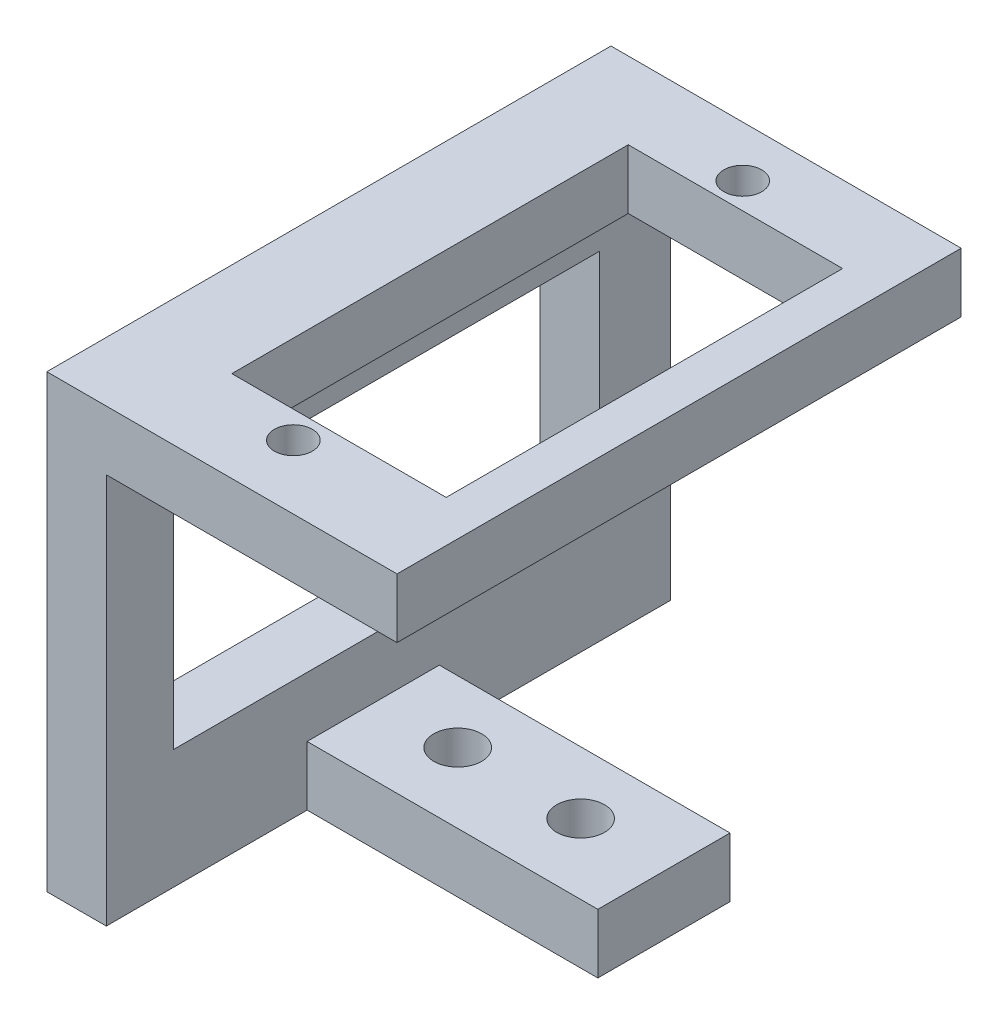
SolidWorks part; units mm, degrees
ref_plane "Front Plane" through (0, 0, 0) normal (0, 0, 1) x (1, 0, 0)
ref_plane "Top Plane" through (0, 0, 0) normal (0, 1, 0) x (1, 0, 0)
ref_plane "Right Plane" through (0, 0, 0) normal (1, 0, 0) x (0, 0, -1)
sketch "Sketch1" plane through (0, 0, 0) normal (0, 0, 1) x (1, 0, 0)
  line L0 (0, 0) -> (0, -20.0603)
  line L1 (0, -20.0603) -> (17.6, -20.0603)
  line L2 (0, 0) -> (17.6, 0)
  dimension "D1" = 20.0603
  dimension "D2" = 17.6
  dimension "D3" = 17.6
extrude "Extrude-Thin1" add sketch "Sketch1" against normal blind 34.1541 thin
sketch "Sketch5" plane through (0, 0, 0) normal (0, 1, 0) x (1, 0, 0)
  line L0 (-3.602, 34.1541) -> (-3.602, 0) construction
  line L1 (2.098, 29.5) -> (15.0763, 29.5)
  line L2 (2.098, 29.5) -> (2.098, 5.5)
  line L3 (2.098, 5.5) -> (15.0763, 5.5)
  line L4 (15.0763, 29.5) -> (15.0763, 5.5)
  line L5 (17.6, 34.1541) -> (17.6, 0) construction
  line L6 (17.6, 0) -> (-3.602, 0) construction
  circle A0 centre (7.453, 31.0775) radius 1.15
  circle A1 centre (7.453, 3.8706) radius 1.15
  point P14 (7.453, 3.8706)
  point P15 (7.453, 31.0775)
  dimension "D5" = 2.3
  dimension "D6" = 2.3
  dimension "D1" = 5.7
  dimension "D2" = 24
  dimension "D3" = 2.5237
  dimension "D4" = 5.5
extrude "Cut-Extrude7" cut sketch "Sketch5" along normal blind 8
sketch "Sketch6" plane through (0, 0, 0) normal (0, 1, 0) x (1, 0, 0)
  line L0 (17.6, 34.1541) -> (-3.602, 34.1541) construction
  line L1 (0, 34.1541) -> (17.6, 34.1541)
  line L2 (0, 34.1541) -> (0, 20.1608)
  line L3 (0, 20.1608) -> (17.6, 20.1608)
  line L4 (17.6, 34.1541) -> (17.6, 20.1608)
  line L5 (17.6, 34.1541) -> (17.6, 0) construction
  line L7 (0, 12.1571) -> (17.6, 12.1571)
  line L8 (0, 12.1571) -> (0, 0)
  line L9 (0, 0) -> (17.6, 0)
  line L10 (17.6, 12.1571) -> (17.6, 0)
extrude "Cut-Extrude8" cut sketch "Sketch6" against normal blind 29
sketch "Sketch7" plane through (0, 0, 0) normal (0, 1, 0) x (1, 0, 0)
  circle A0 centre (4.8804, 16.3944) radius 1.45
  circle A1 centre (12.3192, 16.3944) radius 1.45
  dimension "D1" = 2.9
  dimension "D2" = 2.9
extrude "Cut-Extrude9" cut sketch "Sketch7" against normal blind 33
sketch "Sketch8" plane through (0, 0, 0) normal (1, 0, 0) x (0, 0, -1)
  line L1 (4.0732, -3.2088) -> (29.8553, -3.2088)
  line L2 (4.0732, -3.2088) -> (4.0732, -16.4381)
  line L3 (4.0732, -16.4381) -> (29.8553, -16.4381)
  line L4 (29.8553, -3.2088) -> (29.8553, -16.4381)
extrude "Cut-Extrude10" cut sketch "Sketch8" against normal blind 16
